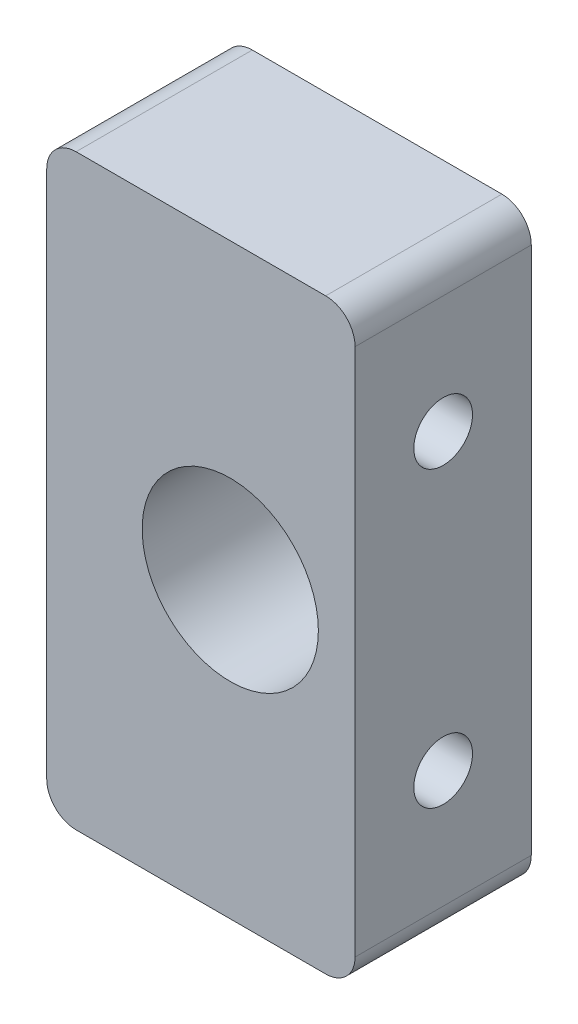
SolidWorks part; units mm, degrees
ref_plane "Front Plane" through (0, 0, 0) normal (0, 0, 1) x (1, 0, 0)
ref_plane "Top Plane" through (0, 0, 0) normal (0, 1, 0) x (1, 0, 0)
ref_plane "Right Plane" through (0, 0, 0) normal (1, 0, 0) x (0, 0, -1)
sketch "Sketch1" plane through (0, 0, 0) normal (0, 0, 1) x (1, 0, 0)
  line L1 (0, 0) -> (21, 0)
  line L2 (0, 0) -> (0, 40)
  line L3 (0, 40) -> (21, 40)
  line L4 (21, 0) -> (21, 40)
  dimension "D1" = 21
  dimension "D2" = 40
extrude "Boss-Extrude1" add sketch "Sketch1" along normal blind 12
sketch "Sketch2" plane through (0, 0, 12) normal (0, 0, 1) x (1, 0, 0)
  line L0 (0, 20) -> (21, 20) construction
  line L1 (0, 40) -> (0, 0) construction
  line L2 (21, 0) -> (21, 40) construction
  circle A0 centre (12.5, 20) radius 6
  dimension "D1" = 12
  dimension "D2" = 2.5
extrude "Cut-Extrude1" cut sketch "Sketch2" against normal up to next
sketch "Sketch3" plane through (0, 0, 0) normal (-1, 0, 0) x (0, 0, 1)
  line L0 (6, 40) -> (6, 0) construction
  line L1 (12, 40) -> (0, 40) construction
  line L2 (12, 0) -> (0, 0) construction
  line L3 (0, 20) -> (12, 20) construction
  line L4 (0, 40) -> (0, 0) construction
  line L5 (12, 40) -> (12, 0) construction
  circle A0 centre (6, 30) radius 2
  circle A1 centre (6, 10) radius 2
  dimension "D1" = 4
  dimension "D2" = 20
extrude "Cut-Extrude2" cut sketch "Sketch3" against normal up to next
sketch "Sketch4" plane through (0, 0, 0) normal (-1, 0, 0) x (0, 0, 1)
  circle A0 centre (6, 30) radius 3.75
  circle A1 centre (6, 10) radius 3.75
  dimension "D1" = 7.5
extrude "Cut-Extrude3" cut sketch "Sketch4" against normal blind 1.5
fillet "Fillet1" radius 2 4 edges at (21, 0, 6) (0, 0, 6) (21, 40, 6) (0, 40, 6)
